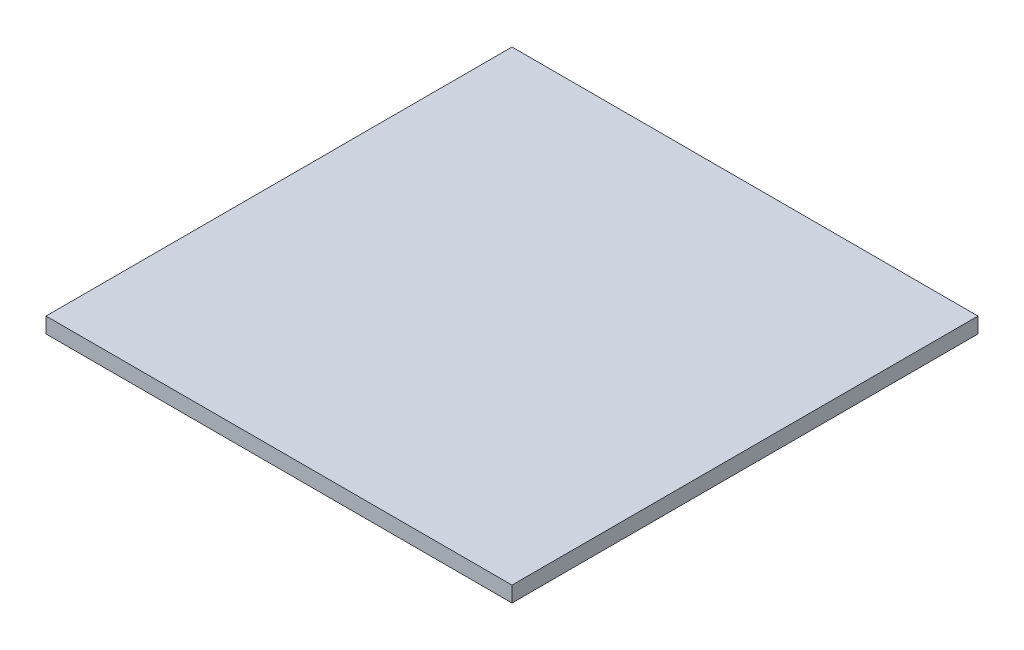
SolidWorks part; units mm, degrees
ref_plane "Front Plane" through (0, 0, 0) normal (0, 0, 1) x (1, 0, 0)
ref_plane "Top Plane" through (0, 0, 0) normal (0, 1, 0) x (1, 0, 0)
ref_plane "Right Plane" through (0, 0, 0) normal (1, 0, 0) x (0, 0, -1)
sketch "Sketch1" plane through (0, 0, 0) normal (0, 0, 1) x (1, 0, 0)
  line L0 (-430.4163, 0) -> (430.4163, 0) construction
  line L1 (0, -313.8614) -> (0, 313.8614) construction
  line L3 (-762, -25.4) -> (762, -25.4)
  line L4 (-762, -25.4) -> (-762, 25.4)
  line L5 (-762, 25.4) -> (762, 25.4)
  line L6 (762, -25.4) -> (762, 25.4)
  line L7 (-762, -25.4) -> (762, 25.4) construction
  line L8 (-762, 25.4) -> (762, -25.4) construction
  point P0 (0, 0)
  point P4 (0, 0)
  point P8 (0, 0)
  dimension "D1" = 1524
  dimension "D2" = 50.8
extrude "Boss-Extrude1" add sketch "Sketch1" along normal mid plane 1524
